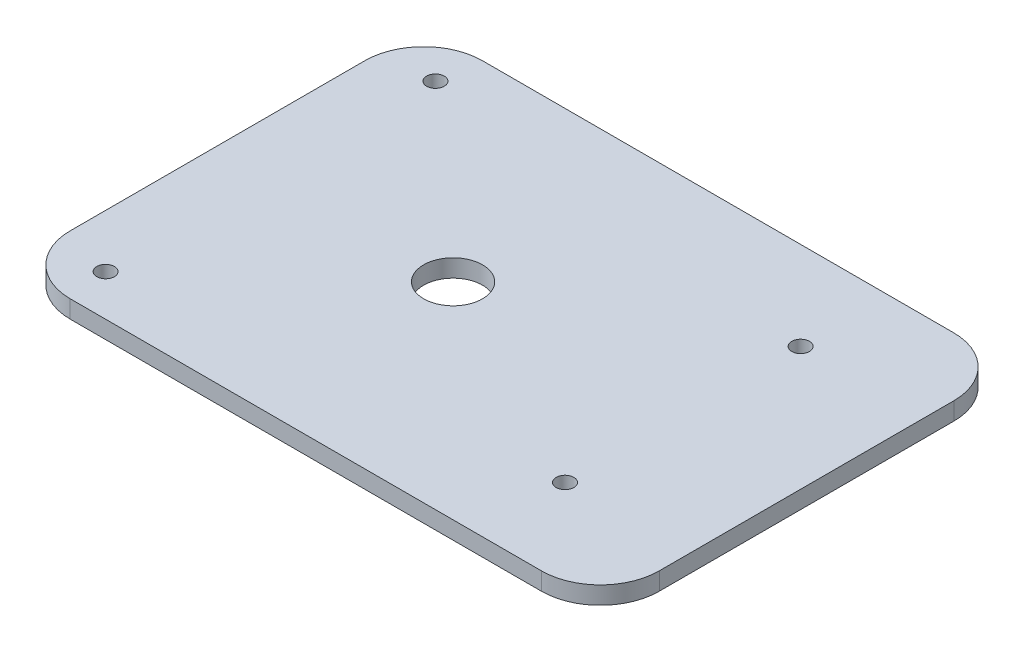
SolidWorks part; units mm, degrees
ref_plane "前视基准面" through (0, 0, 0) normal (0, 0, 1) x (1, 0, 0)
ref_plane "上视基准面" through (0, 0, 0) normal (0, 1, 0) x (1, 0, 0)
ref_plane "右视基准面" through (0, 0, 0) normal (1, 0, 0) x (0, 0, -1)
sketch "草图1" plane through (0, 0, 0) normal (0, 1, 0) x (1, 0, 0)
  line L1 (-40, 35) -> (60, 35)
  line L2 (-40, 35) -> (-40, -35)
  line L3 (-40, -35) -> (60, -35)
  line L4 (60, 35) -> (60, -35)
  dimension "D1" = 100
  dimension "D2" = 40
  dimension "D3" = 70
  dimension "D4" = 35
extrude "凸台-拉伸1" add sketch "草图1" along normal blind 3
fillet "圆角1" radius 10 4 edges at (-40, 1.5, -35) (60, 1.5, -35) (60, 1.5, 35) (-40, 1.5, 35)
sketch "草图2" plane through (0, 3, 0) normal (0, 1, 0) x (1, 0, 0)
  circle A0 centre (0, 0) radius 5
  dimension "D1" = 10
extrude "切除-拉伸1" cut sketch "草图2" against normal through all
sketch "草图3" plane through (0, 3, 0) normal (0, 1, 0) x (1, 0, 0)
  line L1 (-40, 25) -> (-40, -25) construction
  circle A0 centre (-31, 28) radius 1.5
  circle A1 centre (39, 20) radius 1.5
  dimension "D1" = 3
  dimension "D2" = 3
  dimension "D5" = 9
  dimension "D6" = 70
  dimension "D3" = 28
  dimension "D4" = 20
extrude "切除-拉伸2" cut sketch "草图3" against normal through all
mirror "镜向1" about plane through (0, 0, 0) normal (0, 0, 1) of "切除-拉伸2"
